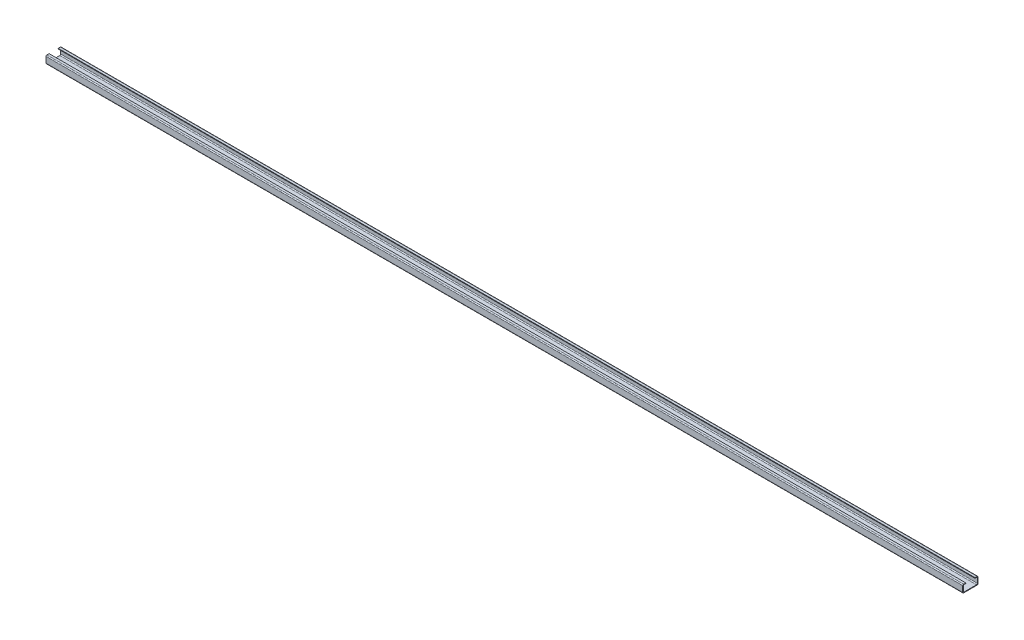
SolidWorks part; units mm, degrees
material "AISI 1045 Aço, trefilado"
ref_plane "Plano frontal" through (0, 0, 0) normal (0, 0, 1) x (1, 0, 0)
ref_plane "Plano superior" through (0, 0, 0) normal (0, 1, 0) x (1, 0, 0)
ref_plane "Plano direito" through (0, 0, 0) normal (1, 0, 0) x (0, 0, -1)
sketch "Esboço1" plane through (0, 0, 0) normal (1, 0, 0) x (0, 0, -1)
  line L0 (-46, 21) -> (-46, -21)
  line L1 (-50, 25) -> (-30, 25)
  line L2 (-50, 25) -> (-50, -25)
  line L3 (-50, -25) -> (50, -25)
  line L4 (50, 25) -> (50, -25)
  line L5 (-50, 25) -> (50, -25) construction
  line L6 (-50, -25) -> (50, 25) construction
  line L7 (-46, -21) -> (46, -21)
  line L8 (46, 21) -> (46, -21)
  line L9 (-46, 21) -> (-30, 21)
  line L10 (-30, 25) -> (-30, 21)
  line L13 (30, 25) -> (30, 21)
  line L14 (30, 21) -> (46, 21)
  line L15 (-46, 21) -> (46, 21) construction
  line L16 (30, 25) -> (50, 25)
  line L17 (-50, 25) -> (50, 25) construction
  point P0 (0, 0)
  dimension "D1" = 100
  dimension "D2" = 50
  dimension "D4" = 20
  dimension "D5" = 20
  dimension "D3" = 4
extrude "Ressalto-extrusão1" add sketch "Esboço1" along normal blind 6000
fillet "Filete1" radius 6 8 edges at (3000, 21, -46) (3000, 21, 46) (3000, 25, 50) (3000, 25, -50) (3000, -25, -50) (3000, -21, -46) (3000, -21, 46) (3000, -25, 50)
